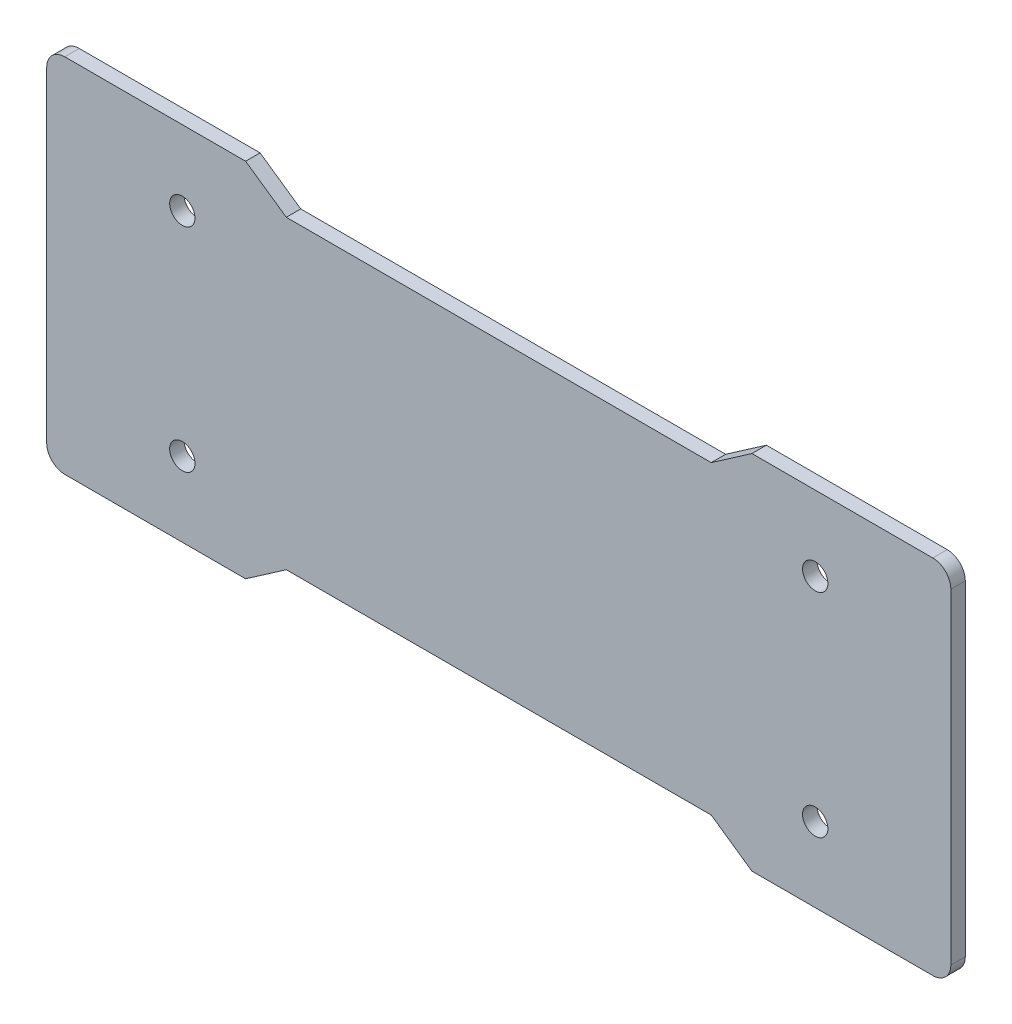
SolidWorks part; units mm, degrees
ref_plane "Front Plane" through (0, 0, 0) normal (0, 0, 1) x (1, 0, 0)
ref_plane "Top Plane" through (0, 0, 0) normal (0, 1, 0) x (1, 0, 0)
ref_plane "Right Plane" through (0, 0, 0) normal (1, 0, 0) x (0, 0, -1)
sketch "Sketch1" plane through (0, 0, 0) normal (0, 0, 1) x (1, 0, 0)
  line L1 (48, -20) -> (-48, -20)
  line L2 (50, -18) -> (50, 18)
  line L3 (48, 20) -> (-48, 20)
  line L4 (-50, -18) -> (-50, 18)
  line L5 (50, -20) -> (-50, 20) construction
  line L6 (50, 20) -> (-50, -20) construction
  arc A0 (50, -18) -> (48, -20) centre (48, -18) cw
  arc A1 (50, 18) -> (48, 20) centre (48, 18) ccw
  arc A2 (-48, -20) -> (-50, -18) centre (-48, -18) cw
  arc A3 (-50, 18) -> (-48, 20) centre (-48, 18) cw
  point P0 (0, 0)
  dimension "D3" = 2
  dimension "D1" = 100
  dimension "D2" = 40
extrude "Boss-Extrude1" add sketch "Sketch1" along normal blind 1.6
ref_plane "Plane1" through (0, 0, 1.6) normal (0, 0, 1) x (1, 0, 0)
sketch "Sketch2" plane through (0, 0, 1.6) normal (0, 0, 1) x (1, 0, 0)
  line L0 (0, 0) -> (0, 16.88) construction
  line L1 (23.5, 16.88) -> (-23.5, 16.88)
  line L2 (0, 16.88) -> (0, 20) construction
  line L3 (48, 20) -> (-48, 20) construction
  line L4 (28, 20) -> (-28, 20)
  line L5 (-28, 20) -> (-23.5, 16.88)
  line L6 (28, 20) -> (23.5, 16.88)
  line L7 (0, 0) -> (-7.0059, 0) construction
  line L8 (28, -20) -> (23.5, -16.88)
  line L9 (23.5, -16.88) -> (-23.5, -16.88)
  line L10 (-28, -20) -> (-23.5, -16.88)
  line L11 (28, -20) -> (-28, -20)
  line L12 (0, 0) -> (-35, 0) construction
  line L13 (-35, 0) -> (-35, 11.75) construction
  circle A0 centre (-35, 11.75) radius 1.4
  circle A1 centre (-35, -11.75) radius 1.4
  circle A2 centre (35, -11.75) radius 1.4
  circle A3 centre (35, 11.75) radius 1.4
  dimension "D6" = 2.8
  dimension "D1" = 16.88
  dimension "D2" = 23.5
  dimension "D3" = 28
  dimension "D4" = 35
  dimension "D5" = 11.75
extrude "Cut-Extrude1" cut sketch "Sketch2" against normal blind 1.6
